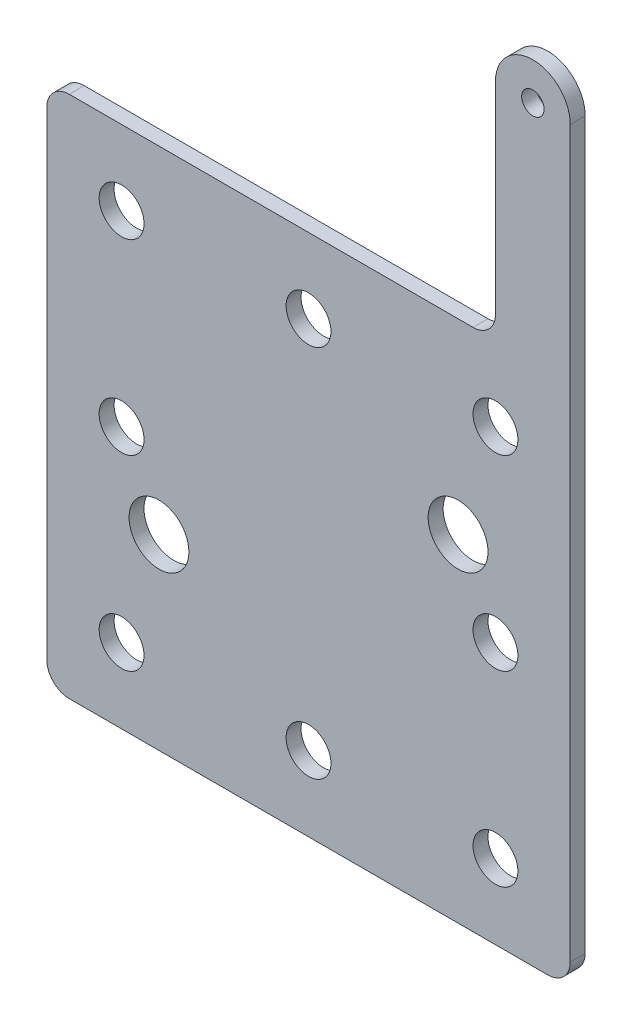
SolidWorks part; units mm, degrees
ref_plane "Front Plane" through (0, 0, 0) normal (0, 0, 1) x (1, 0, 0)
ref_plane "Top Plane" through (0, 0, 0) normal (0, 1, 0) x (1, 0, 0)
ref_plane "Right Plane" through (0, 0, 0) normal (1, 0, 0) x (0, 0, -1)
sketch "Sketch1" plane through (0, 0, 0) normal (0, 0, 1) x (1, 0, 0)
  line L0 (35, 35) -> (35, 65)
  line L1 (-35, -35) -> (35, -35)
  line L2 (-35, -35) -> (-35, 35)
  line L3 (-35, 35) -> (25, 35)
  line L4 (35, -35) -> (35, 35)
  line L7 (25, 35) -> (25, 65)
  arc A0 (25, 65) -> (35, 65) centre (30, 65) cw
  point P0 (0, 0)
  dimension "D1" = 70
  dimension "D2" = 70
  dimension "D3" = 30
  dimension "D4" = 10
extrude "Boss-Extrude1" add sketch "Sketch1" along normal blind 2
sketch "Sketch2" plane through (0, 0, 2) normal (0, 0, 1) x (1, 0, 0)
  circle A0 centre (30, 65) radius 1.5
extrude "Cut-Extrude1" cut sketch "Sketch2" against normal blind 2
sketch "Sketch3" plane through (0, 0, 2) normal (0, 0, 1) x (1, 0, 0)
  line L0 (-35, -35) -> (35, -35) construction
  circle A0 centre (0, 25) radius 3
  circle A1 centre (25, 25) radius 3
  circle A2 centre (25, 0) radius 3
  circle A3 centre (25, -25) radius 3
  circle A4 centre (0, -25) radius 3
  circle A5 centre (-25, -25) radius 3
  circle A6 centre (-25, 0) radius 3
  circle A7 centre (-25, 25) radius 3
  circle A8 centre (-20, -10) radius 4
  circle A9 centre (20, 10) radius 4
  point P0 (0, 0)
  point P12 (0, 0)
  point P15 (0, 0)
  dimension "D3" = 25
  dimension "D5" = 8
  dimension "D1" = 50
  dimension "D2" = 50
extrude "Cut-Extrude2" cut sketch "Sketch3" against normal blind 10
fillet "Fillet1" radius 3 4 edges at (25, 35, 1) (35, -35, 1) (-35, -35, 1) (-35, 35, 1)
sketch "Sketch4" plane through (0, 0, 2) normal (0, 0, 1) x (1, 0, 0)
  line L1 (-15, -15) -> (15, -15)
  line L2 (-15, -15) -> (-15, 15)
  line L3 (-15, 15) -> (15, 15)
  line L4 (15, -15) -> (15, 15)
  line L5 (0, 15) -> (0, -15) construction
  line L6 (-15, 0) -> (15, 0) construction
  point P0 (0, 0)
  dimension "D1" = 30
  dimension "D2" = 30
